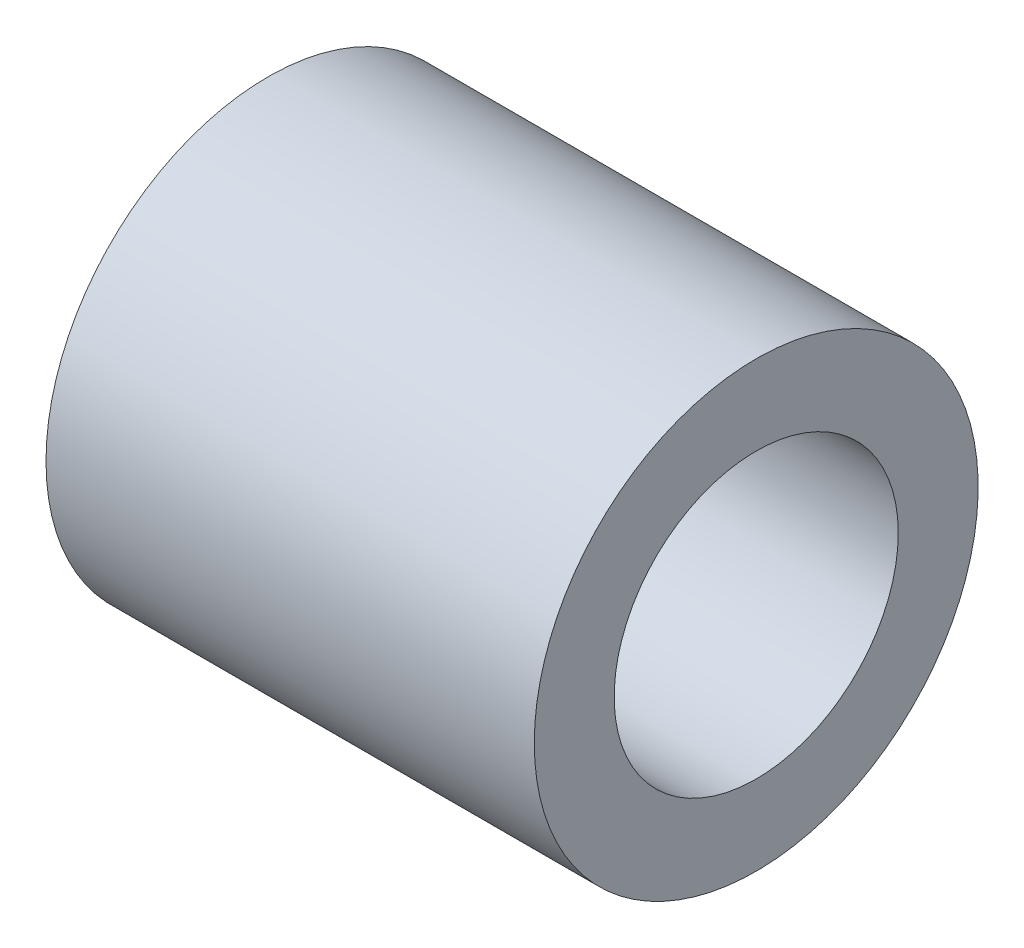
SolidWorks part; units mm, degrees
ref_plane "Front" through (0, 0, 0) normal (0, 0, 1) x (1, 0, 0)
ref_plane "Top" through (0, 0, 0) normal (0, 1, 0) x (1, 0, 0)
ref_plane "Right" through (0, 0, 0) normal (1, 0, 0) x (0, 0, -1)
sketch "Skizze1" plane through (0, 0, 0) normal (0, 0, 1) x (1, 0, 0)
  line L0 (0, 0) -> (15.5597, 0) construction
  line L1 (0, 0) -> (5.5, 0)
  line L2 (0, 0) -> (0, 2.5)
  line L3 (0, 2.5) -> (5.5, 2.5)
  line L4 (5.5, 0) -> (5.5, 2.5)
  dimension "D1" = 5.5
  dimension "D2" = 5
revolve "Rotation1" add sketch "Skizze1" angle 360 about L0
sketch "Skizze2" plane through (5.5, 0, 0) normal (1, 0, 0) x (0, 0, -1)
  circle A0 centre (0, 0) radius 1.6
  dimension "D1" = 3.2
extrude "Schnitt-Linear austragen1" cut sketch "Skizze2" against normal up to surface (5.5 mm away) up to face at (0, 0, 2.5)
